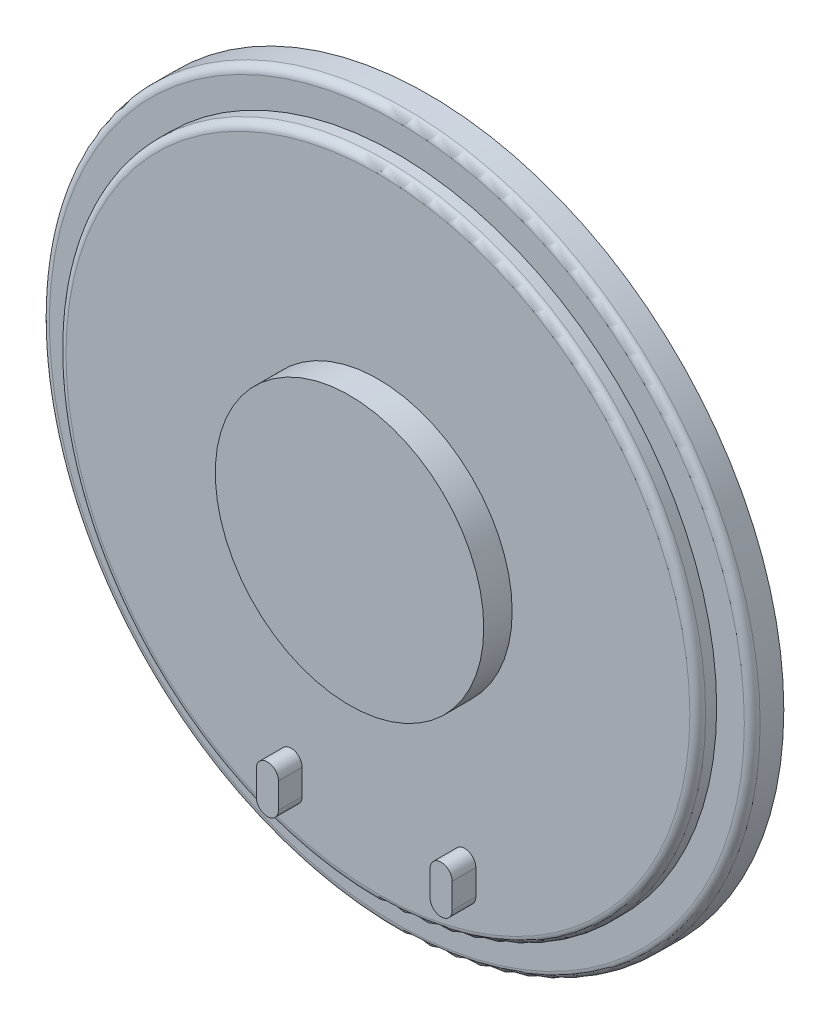
SolidWorks part; units mm, degrees
ref_plane "前视基准面" through (0, 0, 0) normal (0, 0, 1) x (1, 0, 0)
ref_plane "上视基准面" through (0, 0, 0) normal (0, 1, 0) x (1, 0, 0)
ref_plane "右视基准面" through (0, 0, 0) normal (1, 0, 0) x (0, 0, -1)
sketch "草图1" plane through (0, 0, 0) normal (0, 0, 1) x (1, 0, 0)
  circle A0 centre (0, 0) radius 22.5
  dimension "D1" = 45
extrude "拉伸1" add sketch "草图1" along normal blind 5
sketch "草图2" plane through (0, 0, 5) normal (0, 0, 1) x (1, 0, 0)
  circle A0 centre (0, 0) radius 20.25
  dimension "D1" = 40.5
extrude "切除-拉伸1" cut sketch "草图2" against normal offset from surface (3 mm away) 2 flip side to cut up to face at (22.5, 0, 0)
sketch "草图3" plane through (0, 0, 5) normal (0, 0, 1) x (1, 0, 0)
  circle A0 centre (0, 0) radius 8.5
  dimension "D1" = 17
extrude "切除-拉伸2" cut sketch "草图3" against normal blind 1.8 flip side to cut
sketch "草图4" plane through (0, 0, 0) normal (0, 0, -1) x (-1, 0, 0)
  circle A0 centre (0, 0) radius 20.25
  dimension "D1" = 40.5
extrude "切除-拉伸3" cut sketch "草图4" against normal blind 1.8
fillet "圆角1" radius 1.5 1 edges at (-20.25, 0, 0)
fillet "圆角2" radius 0.5 1 edges at (22.5, 0, 2)
fillet "圆角3" radius 0.5 1 edges at (20.25, 0, 3.2)
sketch "草图5" plane through (0, 0, 3.2) normal (0, 0, 1) x (1, 0, 0)
  line L0 (0, 24.0208) -> (0, -25.054) construction
  line L1 (-21.3641, -16) -> (22.8401, -16) construction
  line L2 (-5.5, -15.2) -> (-5.5, -16.8) construction
  line L3 (-4.8, -15.2) -> (-4.8, -16.8)
  line L4 (-6.2, -15.2) -> (-6.2, -16.8)
  line L5 (5.5, -15.2) -> (5.5, -16.8) construction
  line L6 (4.8, -15.2) -> (4.8, -16.8)
  line L7 (6.2, -15.2) -> (6.2, -16.8)
  arc A0 (-4.8, -15.2) -> (-6.2, -15.2) centre (-5.5, -15.2) ccw
  arc A1 (-6.2, -16.8) -> (-4.8, -16.8) centre (-5.5, -16.8) ccw
  arc A2 (4.8, -15.2) -> (6.2, -15.2) centre (5.5, -15.2) cw
  arc A3 (6.2, -16.8) -> (4.8, -16.8) centre (5.5, -16.8) cw
  point P7 (-5.5, -16)
  point P14 (5.5, -16)
  dimension "D1" = 16
  dimension "D2" = 1.4
  dimension "D3" = 1.6
  dimension "D4" = 11
extrude "接线焊盘" add sketch "草图5" along normal blind 1.5
